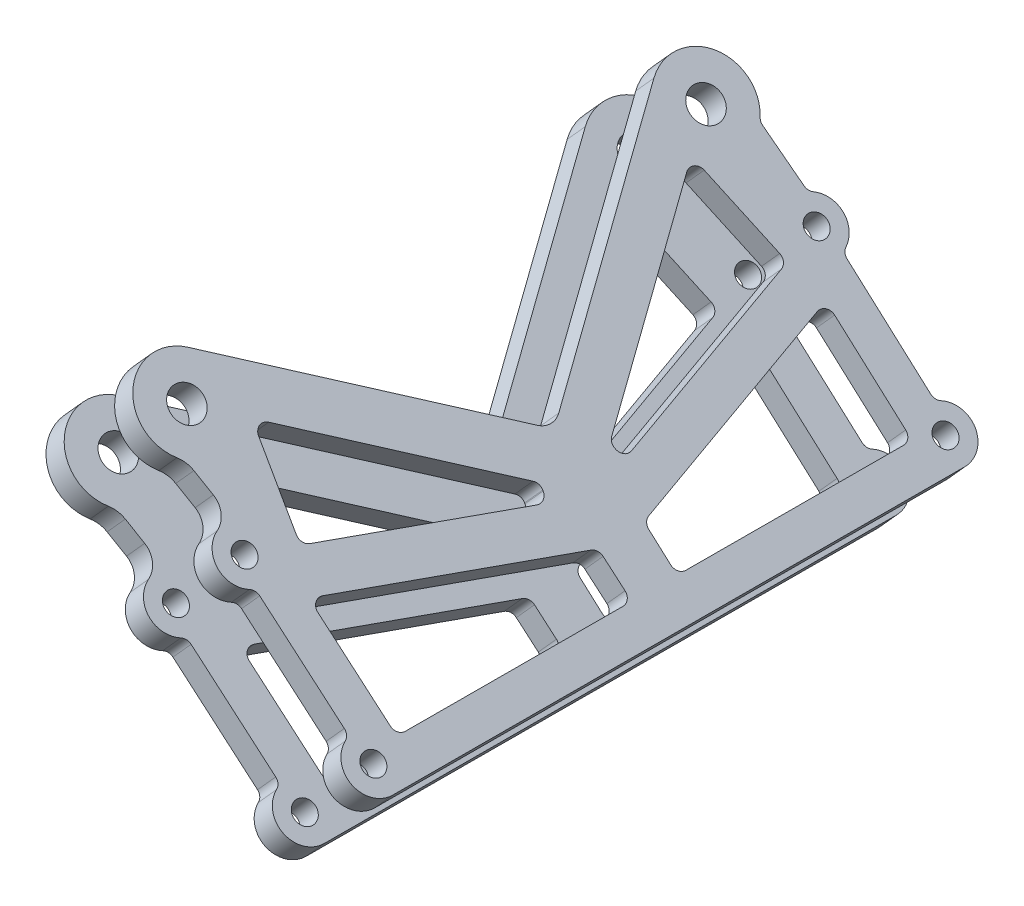
SolidWorks part; units mm, degrees
material "7075-T6, Plate (SS)"
ref_plane "Ground Plane" through (0, 0, 0) normal (0, 0, 1) x (1, 0, 0)
ref_plane "Side Plane" through (0, 0, 0) normal (0, 1, 0) x (1, 0, 0)
ref_plane "Rear Axle Centerline" through (0, 0, 0) normal (1, 0, 0) x (0, 0, -1)
sketch "Chassis Side View" plane through (0, 0, 0) normal (0, 1, 0) x (1, 0, 0)
  line L0 (0, -381) -> (2300, -381) construction
  line L1 (1150, -381) -> (1150, -856.742)
  line L2 (2150, -381) -> (2150, -1062.9307) construction
  line L3 (-753.0356, 0) -> (753.0356, 0) construction
  line L4 (2450, -381) -> (2450, -1062.9307) construction
  dimension "D1" = 2300
  dimension "D2" = 475.742
  dimension "D3" = 1150
  dimension "D4" = 381
  dimension "D5" = 150
  dimension "D6" = 150
ref_plane "Front Axle Centerline" through (2300, 0, 0) normal (1, 0, 0) x (0, 0, -1)
sketch "Front Wheel Assy Constraints" plane through (2300, 0, 0) normal (1, 0, 0) x (0, 0, -1)
  line L0 (0, 727.5) -> (0, 822.5)
  line L1 (0, 822.5) -> (-271.78, 822.5)
  line L2 (-271.78, 822.5) -> (-551.18, 822.5)
  line L3 (-551.18, 822.5) -> (-551.18, 727.5)
  line L4 (-551.18, 775) -> (0, 775) construction
  line L5 (-271.78, 822.5) -> (-271.78, 775) construction
  line L6 (-551.18, 727.5) -> (-445.4516, 727.5)
  line L7 (-445.4516, 727.5) -> (-445.4516, 798.5)
  line L8 (-445.4516, 798.5) -> (-105.7284, 798.5)
  line L9 (-105.7284, 798.5) -> (-105.7284, 727.5)
  line L10 (-105.7284, 727.5) -> (0, 727.5)
  line L11 (0, 0) -> (-673.9047, 0) construction
  line L13 (0, 753.0356) -> (0, -753.0356) construction
  dimension "D1" = 95
  dimension "D2" = 279.4
  dimension "D3" = 271.78
  dimension "D4" = 23.5
  dimension "D5" = 1550
sketch "Front Sus Front View" plane through (2300, 0, 0) normal (1, 0, 0) x (0, 0, -1)
  line L0 (0, 775) -> (0, 768.65) construction
  line L1 (0, 753.0356) -> (0, -753.0356) construction
  line L2 (0, 768.65) -> (-762, 634.2888) construction
  line L3 (0, 768.65) -> (-745.3671, 768.65) construction
  line L4 (-366.7919, -1090.2477) -> (-525.9451, 520.8571) construction
  line L5 (-366.7919, -1090.2477) -> (-379.5678, 520.8571) construction
  line L6 (-366.7919, -1090.2477) -> (0, 775) construction
  line L7 (-525.9451, 520.8571) -> (-541, 673.2571)
  line L8 (-379.5678, 520.8571) -> (-381, 701.4694)
  line L9 (0, 0) -> (-152.4, 0) construction
  line L13 (-525.9451, 520.8571) -> (-379.5678, 520.8571) construction
  dimension "D1" = 6.35
  dimension "D2" = 10
  dimension "D3" = 152.4
  dimension "D4" = 1865.2477
  dimension "D6" = 381
  dimension "D7" = 541
  dimension "D8" = 153.1418
  dimension "D5" = 152.4
ref_plane "Fron Wheel Side View Plane" through (0, 775, 0) normal (0, 1, 0) x (1, 0, 0)
sketch "Front SVSA" plane through (0, 775, 0) normal (0, 1, 0) x (1, 0, 0)
  line L0 (2271.684, -676.7175) -> (2328.316, 133.1575)
  line L1 (2300, 0) -> (2300, -771.0839) construction
  line L2 (2300, 0) -> (-2450.054, -116.0888) construction
  line L3 (-2450.054, -116.0888) -> (2298.2335, -297.0415) construction
  line L4 (-753.0356, 0) -> (753.0356, 0) construction
  point P5 (2300, -271.78)
  dimension "D1" = 4
  dimension "D2" = 1.4
  dimension "D3" = 4750.054
sketch3d "Front Chassis Side Axes"
  line L0 (2300, 520.8571, 379.5678) -> (2300, 701.4694, 381) construction
  line L1 (2300, 520.8571, 525.9451) -> (2300, 673.2571, 541) construction
  line L2 (2300, 520.8571, 379.5678) -> (2300, 701.4694, 381) construction
  line L3 (2300, 520.8571, 525.9451) -> (2300, 673.2571, 541) construction
  line L4 (2300, 673.2571, 541) -> (2300, 775, 551.0507) construction
  line L5 (2300, 701.4694, 381) -> (2300, 775, 381.5831) construction
  line L6 (2300, 775, 0) -> (2300, 775, 771.0839) construction
  line L7 (-2450.054, 775, 116.0888) -> (2349.7917, 775, 555.6101) construction
  line L8 (-2450.054, 775, 116.0888) -> (2349.9221, 775, 384.3734) construction
  line L9 (2349.9221, 775, 384.3734) -> (2177.377, 520.8571, 372.714) construction
  line L10 (2349.7917, 775, 555.6101) -> (2225.4174, 520.8571, 519.1156) construction
  line L11 (2300, 520.8571, 525.9451) -> (2300, 520.8571, 519.1156) construction
  line L12 (2300, 520.8571, 519.1156) -> (2225.4174, 520.8571, 519.1156) construction
  line L13 (2598.7501, 520.8571, 553.3017) -> (1702.4998, 520.8571, 471.2321)
  line L14 (2300, 520.8571, 379.5678) -> (2300, 520.8571, 372.714) construction
  line L15 (2300, 520.8571, 372.714) -> (2177.377, 520.8571, 372.714) construction
  line L16 (2599.5325, 520.8571, 396.3095) -> (1700.935, 520.8571, 346.0843)
  dimension "D1" = 50
  dimension "D2" = 50
  dimension "D3" = 600
  dimension "D4" = 300
  dimension "D5" = 600
  dimension "D6" = 300
sketch3d "Front Left Control Arm"
  line L0 (2300, 520.8571, 379.5678) -> (2300, 701.4694, 381) construction
  line L2 (2300, 520.8571, 379.5678) -> (2300, 701.4694, 381) construction
  line L3 (2300, 520.8571, 525.9451) -> (2300, 673.2571, 541) construction
  line L4 (2598.7501, 520.8571, 553.3017) -> (1702.4998, 520.8571, 471.2321) construction
  line L5 (2599.5325, 520.8571, 396.3095) -> (1700.935, 520.8571, 346.0843) construction
  line L6 (2598.7501, 520.8571, 553.3017) -> (1702.4998, 520.8571, 471.2321) construction
  line L7 (2599.5325, 520.8571, 396.3095) -> (1700.935, 520.8571, 346.0843) construction
  line L8 (2450, 520.8571, 539.6806) -> (2280.5957, 673.2571, 539.2232)
  line L9 (2280.5957, 673.2571, 539.2232) -> (2150, 520.8571, 512.2097)
  line L10 (2300, 520.8571, 525.9451) -> (2300, 673.2571, 541) construction
  line L11 (2300, 673.2571, 541) -> (2280.5957, 673.2571, 539.2232) construction
  line L12 (2271.684, 775, 676.7175) -> (2328.316, 775, -133.1575) construction
  line L13 (2150, 0, 512.2097) -> (2150, 520.8571, 512.2097) construction
  line L14 (2292.3517, 701.4694, 380.5725) -> (2292.3517, 775, 381.1556) construction
  line L15 (2150, 0, 381) -> (2150, 0, 1062.9307) construction
  line L16 (2450, 0, 539.6806) -> (2450, 520.8571, 539.6806) construction
  line L17 (2450, 0, 381) -> (2450, 0, 1062.9307) construction
  line L18 (2450, 520.8571, 387.9517) -> (2292.3517, 701.4694, 380.5725)
  line L19 (2292.3517, 701.4694, 380.5725) -> (2150, 520.8571, 371.1838)
  line L20 (2300, 701.4694, 381) -> (2292.3517, 701.4694, 380.5725) construction
  line L21 (2450, 0, 387.9517) -> (2450, 520.8571, 387.9517) construction
  line L22 (2150, 0, 371.1838) -> (2150, 520.8571, 371.1838) construction
  line L23 (2280.5957, 673.2571, 539.2232) -> (2280.5957, 775, 549.2738) construction
sketch3d "Front Control Arm"
  line L0 (2450, 520.8571, 387.9517) -> (2292.3517, 701.4694, 380.5725) construction
  line L1 (2292.3517, 701.4694, 380.5725) -> (2150, 520.8571, 371.1838) construction
  line L2 (2280.5957, 673.2571, 539.2232) -> (2150, 520.8571, 512.2097) construction
  line L3 (2450, 520.8571, 539.6806) -> (2280.5957, 673.2571, 539.2232) construction
  line L4 (2450, 520.8571, 387.9517) -> (2292.3517, 701.4694, 380.5725)
  line L5 (2292.3517, 701.4694, 380.5725) -> (2150, 520.8571, 371.1838)
  line L6 (2280.5957, 673.2571, 539.2232) -> (2150, 520.8571, 512.2097)
  line L7 (2450, 520.8571, 539.6806) -> (2280.5957, 673.2571, 539.2232)
  line L8 (2450, -520.8571, 539.6806) -> (2280.5957, -673.2571, 539.2232)
  line L9 (2280.5957, -673.2571, 539.2232) -> (2150, -520.8571, 512.2097)
  line L10 (2292.3517, -701.4694, 380.5725) -> (2150, -520.8571, 371.1838)
  line L11 (2450, -520.8571, 387.9517) -> (2292.3517, -701.4694, 380.5725)
ref_plane "Max Droop Plane" through (0, 0, -25.4) normal (0, 0, 1) x (1, 0, 0)
sketch3d "Shock"
  line L0 (2292.3517, 701.4694, 380.5725) -> (2293.5626, 664.4705, 414.2387) construction
  line L1 (2300, 520.8571, 525.9451) -> (2298.2629, 520.8571, 544.9158) construction
  line L2 (2150, 520.8571, 512.2097) -> (2450, 520.8571, 539.6806) construction
  line L3 (2300, 520.8571, 525.9451) -> (2300, 230.5152, 525.9451) construction
  line L4 (2293.5626, 664.4705, 414.2387) -> (2298.2629, 520.8571, 544.9158)
  dimension "D1" = 50.038
  dimension "D2" = 19.05
sketch3d "Parametric Analysis"
  line L2 (2300, 822.5, 0) -> (2300, 822.5, 271.78) construction
  line L3 (2300.4137, 822.5, 271.7939) -> (2300.4137, 822.5, -88.8537) construction
  line L4 (2450, 520.8571, 387.9517) -> (2292.3526, 701.4695, 380.5568)
  line L5 (2292.3526, 701.4695, 380.5568) -> (2150, 520.8571, 371.1838)
  line L6 (2450, 520.8571, 539.6806) -> (2280.5972, 673.2586, 539.2077)
  line L7 (2280.5972, 673.2586, 539.2077) -> (2150, 520.8571, 512.2097)
  line L8 (2292.3517, 701.4694, 380.5725) -> (2300, 822.5, 271.78) construction
  line L9 (2450, 520.8571, 387.9517) -> (2292.3517, 701.4694, 380.5725) construction
  line L10 (2292.3517, 701.4694, 380.5725) -> (2150, 520.8571, 371.1838) construction
  line L11 (2450, 520.8571, 539.6806) -> (2280.5957, 673.2571, 539.2232) construction
  line L12 (2280.5957, 673.2571, 539.2232) -> (2150, 520.8571, 512.2097) construction
  line L13 (2280.5957, 673.2571, 539.2232) -> (2292.3517, 701.4694, 380.5725) construction
  line L14 (2300, 822.5, 271.78) -> (2280.5957, 673.2571, 539.2232) construction
  line L15 (2300, 822.5, 271.78) -> (2300.4132, 720.8156, 271.78) construction
  line L16 (2280.5972, 673.2586, 539.2077) -> (2300.4137, 822.5, 271.7939) construction
  line L17 (2300.4137, 822.5, 271.7939) -> (2292.3526, 701.4695, 380.5568) construction
  line L18 (2280.5972, 673.2586, 539.2077) -> (2292.3526, 701.4695, 380.5568) construction
  line L19 (2300.4137, 822.5, 271.7939) -> (2300.4137, 720.8148, 271.7641) construction
  line L23 (2292.3517, 701.4694, 380.5725) -> (2265.8007, 667.7821, 378.8214) construction
  line L30 (2265.8007, 667.7821, 378.8214) -> (2325.2406, 663.7898, 382.112) construction
  line L31 (2325.2406, 663.7898, 382.112) -> (2293.5626, 664.4705, 414.2387) construction
  line L32 (2292.3517, 701.4694, 380.5725) -> (2325.2406, 663.7898, 382.112) construction
  line L33 (2293.5626, 664.4705, 414.2387) -> (2265.8007, 667.7821, 378.8214) construction
  line L34 (2292.3526, 701.4695, 380.5568) -> (2293.5633, 664.4722, 414.2247) construction
  line L35 (2292.3517, 701.4694, 380.5725) -> (2293.5626, 664.4705, 414.2387) construction
  line L39 (2300.4137, 822.5, 271.7939) -> (2300.4137, 822.5798, 0.014)
  line L40 (2300.4137, 822.5798, 0.014) -> (2300.4137, 727.5798, -0.014)
  line L41 (2300, 727.5, 0) -> (2300, 822.5, 0) construction
  line L42 (2298.2629, 520.8571, 544.9158) -> (2293.5633, 664.4722, 414.2247)
  point P5 (2300.4137, 775.0798, 0)
  dimension "D1" = 25.4
  dimension "D2" = 194.2357
  dimension "D3" = 0.0798
  dimension "D4" = 0.017
sketch3d "3DSketch1"
  line L0 (2293.5626, 664.4705, 414.2387) -> (2298.2629, 520.8571, 544.9158) construction
  line L1 (2280.5972, 673.2586, 539.2077) -> (2150, 520.8571, 512.2097) construction
  line L2 (2450, 520.8571, 539.6806) -> (2280.5972, 673.2586, 539.2077) construction
  line L3 (2292.3526, 701.4695, 380.5568) -> (2150, 520.8571, 371.1838) construction
  line L4 (2450, 520.8571, 387.9517) -> (2292.3526, 701.4695, 380.5568) construction
  line L5 (2293.5626, 664.4705, 414.2387) -> (2298.2629, 520.8571, 544.9158)
  line L6 (2280.5972, 673.2586, 539.2077) -> (2150, 520.8571, 512.2097)
  line L7 (2450, 520.8571, 539.6806) -> (2280.5972, 673.2586, 539.2077)
  line L8 (2292.3526, 701.4695, 380.5568) -> (2150, 520.8571, 371.1838)
  line L9 (2450, 520.8571, 387.9517) -> (2292.3526, 701.4695, 380.5568)
  line L10 (2450, 520.8571, 539.6806) -> (2450, 470.0571, 539.6806) construction
  line L11 (2150, 520.8571, 512.2097) -> (2150, 470.0571, 512.2097) construction
  line L12 (2298.2629, 520.8571, 544.9158) -> (2298.2629, 470.0571, 544.9158) construction
  line L13 (2450, 520.8571, 387.9517) -> (2450, 470.0571, 387.9517) construction
  line L14 (2150, 520.8571, 371.1838) -> (2150, 470.0571, 371.1838) construction
  line L15 (2150, -520.8571, 512.2097) -> (2150, -470.0571, 512.2097) construction
  line L16 (2298.2629, -520.8571, 544.9158) -> (2298.2629, -470.0571, 544.9158) construction
  line L17 (2450, -520.8571, 539.6806) -> (2450, -470.0571, 539.6806) construction
  line L18 (2293.5626, -664.4705, 414.2387) -> (2298.2629, -520.8571, 544.9158)
  line L19 (2280.5972, -673.2586, 539.2077) -> (2150, -520.8571, 512.2097)
  line L20 (2450, -520.8571, 539.6806) -> (2280.5972, -673.2586, 539.2077)
  line L21 (2450, -520.8571, 387.9517) -> (2450, -470.0571, 387.9517) construction
  line L22 (2150, -520.8571, 371.1838) -> (2150, -470.0571, 371.1838) construction
  line L23 (2292.3526, -701.4695, 380.5568) -> (2150, -520.8571, 371.1838)
  line L24 (2450, -520.8571, 387.9517) -> (2292.3526, -701.4695, 380.5568)
  line L25 (2280.5972, 673.2586, 539.2077) -> (2280.5972, 673.2586, 216.3834) construction
  line L26 (2450, 520.8571, 539.6806) -> (2457.3728, 529.0523, 539.6794) construction
  line L27 (2300, 775, 551.18) -> (2300, 775, 0) construction
  line L29 (2457.3728, 529.0523, 539.6794) -> (2420.3829, 562.3299, 539.5762) construction
  dimension "D1" = 50.8
  dimension "D2" = 304.9478
  dimension "D3" = 544.9185
  dimension "D4" = 11.0236
ref_plane "Plane1" through (0, 718.612, 0) normal (0, 1, 0) x (1, 0, 0)
ref_plane "Plane2" through (1354.9026, 1506.0502, 0) normal (0.6688, 0.7434, 0) x (-0.7434, 0.6688, -0.0021)
sketch "Sketch1" plane through (1354.9026, 1506.0502, 0) normal (0.6688, 0.7434, 0) x (-0.7434, 0.6688, -0.0021)
  line L0 (-1474.1559, 536.6223) -> (-1473.841, 384.8937) construction
  line L1 (-1474.1559, 536.6223) -> (-1474.1559, 558.2123) construction
  line L2 (-1452.5659, 536.6223) -> (-1474.1559, 558.2123)
  line L3 (-1474.1559, 536.6223) -> (-1246.288, 536.6223) construction
  line L4 (-1474.1559, 558.2123) -> (-1575.7559, 558.2123)
  line L5 (-1575.7559, 558.2123) -> (-1575.7559, 363.3037)
  line L10 (-1474.1559, 536.6223) -> (-1452.5659, 536.6223) construction
  line L11 (-1473.841, 384.8937) -> (-1435.1122, 384.9741) construction
  line L12 (-1473.841, 384.8937) -> (-1507.8168, 384.8232) construction
  line L13 (-1452.5659, 536.6223) -> (-1452.5659, 384.9379)
  line L15 (-1473.841, 384.8937) -> (-1473.841, 363.3037) construction
  line L16 (-1575.7559, 363.3037) -> (-1473.841, 363.3037)
  line L17 (-1473.841, 363.3037) -> (-1452.5659, 384.9379)
  line L18 (-1445.7366, 460.758) -> (-1502.2603, 460.758) construction
  circle A0 centre (-1474.1559, 536.6223) radius 4.7625
  circle A1 centre (-1473.841, 384.8937) radius 4.7625
  circle A2 centre (-1557.9759, 544.2423) radius 3.175
  circle A3 centre (-1507.1759, 544.2423) radius 3.175
  circle A4 centre (-1507.1759, 377.2737) radius 3.175
  circle A5 centre (-1557.9759, 377.2737) radius 3.175
  circle A6 centre (-1532.5759, 460.758) radius 3.175
  point P22 (-1473.9984, 460.758)
  point P31 (-1532.5759, 460.758)
  dimension "D1" = 9.525
  dimension "D2" = 9.525
  dimension "D7" = 6.35
  dimension "D10" = 6.35
  dimension "D12" = 6.35
  dimension "D3" = 21.59
  dimension "D4" = 21.59
  dimension "D5" = 21.59
  dimension "D6" = 101.6
  dimension "D8" = 17.78
  dimension "D9" = 13.97
  dimension "D11" = 50.8
  dimension "D13" = 43.18
  dimension "D14" = 97.4543
extrude "Boss-Extrude1" add sketch "Sketch1" along normal blind 18.9611 and the other way blind 18.9611
ref_plane "Cut Plane" through (1367.5841, 1520.1464, 0) normal (0.6688, 0.7434, 0) x (0.7434, -0.6688, 0)
sketch "Sketch2" plane through (1367.5841, 1520.1464, 0) normal (0.6688, 0.7434, 0) x (0.7434, -0.6688, 0)
  line L0 (1556.843, -547.4746) -> (1531.6163, -463.9377) construction
  line L1 (1531.6163, -463.9377) -> (1506.0431, -547.3691) construction
  line L2 (1506.0431, -547.3691) -> (1473.039, -539.6806) construction
  line L3 (1531.6163, -463.9377) -> (1557.1895, -380.5063) construction
  line L4 (1531.6163, -463.9377) -> (1506.3896, -380.4009) construction
  line L5 (1506.3896, -380.4009) -> (1473.039, -387.9517) construction
  line L6 (1473.039, -387.9517) -> (1531.6163, -463.9377) construction
  line L7 (1531.6163, -463.9377) -> (1473.039, -539.6806) construction
  line L8 (1564.8095, -380.5063) -> (1564.463, -547.4746)
  line L9 (1506.0431, -547.3691) -> (1513.3285, -549.6023) construction
  line L10 (1506.0431, -547.3691) -> (1498.7577, -545.136) construction
  line L11 (1473.039, -539.6806) -> (1462.9928, -531.9112) construction
  line L12 (1515.3747, -378.198) -> (1548.2609, -378.198)
  line L13 (1513.6843, -378.198) -> (1499.095, -382.6038) construction
  line L14 (1483.0972, -380.1979) -> (1462.9808, -395.7055) construction
  line L16 (1492.0841, -546.1214) -> (1485.7226, -547.0606)
  line L18 (1482.702, -378.5846) -> (1497.8198, -377.7153)
  line L19 (1507.8037, -533.5519) -> (1486.2159, -528.5229)
  line L28 (1462.9928, -531.9112) -> (1513.1623, -467.04)
  line L29 (1513.1677, -460.8314) -> (1462.9808, -395.7055)
  line L30 (1484.7829, -524.4953) -> (1522.7158, -475.4465)
  line L31 (1525.3013, -474.5266) -> (1525.5167, -474.5767)
  line L32 (1527.3689, -477.7949) -> (1510.8084, -531.8225)
  line L33 (1507.4206, -391.9812) -> (1484.6718, -397.1317)
  line L34 (1483.221, -401.1598) -> (1522.7938, -452.4933)
  line L35 (1525.3664, -453.4198) -> (1525.5847, -453.3704)
  line L36 (1527.4553, -450.1588) -> (1510.413, -393.7242)
  line L37 (1574.594, -561.4814) -> (1472.9942, -561.2706)
  line L38 (1472.9942, -561.2706) -> (1451.449, -539.6358)
  line L39 (1451.449, -539.6358) -> (1451.7638, -387.9517)
  line L40 (1451.7638, -387.9517) -> (1473.0838, -366.3618)
  line L41 (1473.0838, -366.3618) -> (1574.9985, -366.5733)
  line L42 (1574.9985, -366.5733) -> (1574.594, -561.4814)
  line L43 (1514.9847, -549.5748) -> (1547.5052, -549.0356)
  arc A1 (1512.7809, -550.9281) -> (1498.935, -550.115) centre (1506.0431, -547.3691) cw
  arc A2 (1462.9928, -531.9112) -> (1481.6619, -549.0046) centre (1473.039, -539.6806) ccw
  arc A4 (1513.1284, -376.8438) -> (1499.8529, -376.4848) centre (1506.3896, -380.4009) ccw
  arc A5 (1462.9808, -395.7055) -> (1480.97, -378.0326) centre (1473.039, -387.9517) cw
  arc A8 (1492.0841, -546.1214) -> (1498.935, -550.115) centre (1493.0117, -552.4033) cw
  arc A9 (1481.6619, -549.0046) -> (1485.7226, -547.0606) centre (1486.8356, -554.5989) cw
  arc A10 (1484.7829, -524.4953) -> (1486.2159, -528.5229) centre (1486.7921, -526.0491) ccw
  arc A11 (1507.8037, -533.5519) -> (1510.8084, -531.8225) centre (1508.3799, -531.0782) ccw
  arc A12 (1527.3689, -477.7949) -> (1525.5167, -474.5767) centre (1524.9404, -477.0505) ccw
  arc A13 (1525.3013, -474.5266) -> (1522.7158, -475.4465) centre (1524.725, -477.0003) ccw
  arc A14 (1510.413, -393.7242) -> (1507.4206, -391.9812) centre (1507.9815, -394.4585) ccw
  arc A15 (1484.6718, -397.1317) -> (1483.221, -401.1598) centre (1485.2327, -399.609) ccw
  arc A16 (1522.7938, -452.4933) -> (1525.3664, -453.4198) centre (1524.8055, -450.9425) ccw
  arc A17 (1525.5847, -453.3704) -> (1527.4553, -450.1588) centre (1525.0238, -450.8931) ccw
  arc A19 (1513.1623, -467.04) -> (1513.1677, -460.8314) centre (1509.1438, -463.9322) ccw
  arc A22 (1499.8529, -376.4848) -> (1497.8198, -377.7153) centre (1497.674, -375.1795) cw
  arc A23 (1482.702, -378.5846) -> (1480.97, -378.0326) centre (1482.5562, -376.0488) cw
  circle A24 centre (1557.1895, -380.5063) radius 7.62 construction
  circle A25 centre (1556.843, -547.4746) radius 7.62 construction
  arc A26 (1549.8712, -550.5501) -> (1564.463, -547.4746) centre (1556.843, -547.4746) ccw
  arc A27 (1564.8095, -380.5063) -> (1550.4931, -376.8701) centre (1557.1895, -380.5063) ccw
  arc A28 (1549.8712, -550.5501) -> (1547.5052, -549.0356) centre (1547.5473, -551.5753) ccw
  arc A29 (1514.9847, -549.5748) -> (1512.7809, -550.9281) centre (1515.0269, -552.1144) ccw
  arc A30 (1550.4931, -376.8701) -> (1548.2609, -378.198) centre (1548.2609, -375.658) cw
  arc A31 (1515.3747, -378.198) -> (1513.1284, -376.8438) centre (1515.3747, -375.658) cw
  point P17 (1556.843, -547.4746)
  point P25 (1557.1895, -380.5063)
  point P29 (1506.3896, -380.4009)
  point P33 (1473.039, -387.9517)
  point P36 (1483.0972, -380.1979)
  point P37 (1499.291, -377.6307)
  point P39 (1499.095, -382.6038)
  point P48 (1531.6163, -463.9377)
  point P52 (1531.6163, -463.9377)
  point P54 (1531.6163, -463.9377)
  point P62 (1482.3623, -527.6252)
  point P65 (1510.1134, -534.09)
  point P68 (1528.1661, -475.1939)
  point P71 (1523.7133, -474.1566)
  point P74 (1509.7289, -391.4586)
  point P77 (1480.7928, -398.0099)
  point P80 (1523.7842, -453.778)
  point P83 (1528.2434, -452.7685)
  point P84 (1549.3782, -549.0046)
  point P89 (1515.5615, -463.9377)
  point P93 (1549.9276, -378.198)
  point P109 (1481.6788, -378.6434)
  dimension "D2" = 7.62
  dimension "D3" = 12.7
  dimension "D4" = 15.24
  dimension "D5" = 7.62
  dimension "D6" = 12.7
  dimension "D7" = 25.3127
  dimension "D8" = 17.6413
  dimension "D9" = 6.35
  dimension "D10" = 7.62
  dimension "D23" = 2.54
  dimension "D26" = 2.54
  dimension "D11" = 15.24
  dimension "D13" = 2.54
  dimension "D12" = 36.0496
  dimension "D14" = 20.127
  dimension "D15" = 86.1415
  dimension "D18" = 85.9294
  dimension "D19" = 15.24
  dimension "D20" = 4.572
  dimension "D21" = 12.7
  dimension "D22" = 4.572
extrude "Cut-Extrude1" cut sketch "Sketch2" against normal through all
ref_plane "Plane4" through (871.9396, -784.4315, 907.0589) normal (-0.5881, 0.5291, -0.6118) x (-0.8088, -0.3847, 0.4448)
sketch "Sketch3" plane through (871.9396, -784.4315, 907.0589) normal (-0.5881, 0.5291, -0.6118) x (-0.8088, -0.3847, 0.4448)
  line L0 (-1941.8721, 746.988) -> (-1958.1391, 723.0664) construction
  line L2 (-1938.9644, 770.8679) -> (-1920.7331, 758.4704)
  line L3 (-1926.1928, 736.3259) -> (-1957.5515, 757.6502) construction
  line L4 (-1938.9644, 770.8679) -> (-2068.0084, 581.1008)
  line L5 (-2068.0084, 581.1008) -> (-2049.7771, 568.7032)
  line L6 (-2049.7771, 568.7032) -> (-1920.7331, 758.4704)
  point P8 (-1941.8721, 746.988)
  point P9 (-1929.8488, 764.6691)
  dimension "D1" = 11.0236
extrude "Cut-Extrude3" cut sketch "Sketch3" against normal through all both and the other way through all
sketch "Sketch4" plane through (1367.5841, 1520.1464, 0) normal (0.6688, 0.7434, 0) x (0.7434, -0.6688, 0)
  line L0 (1524.1527, -388.358) -> (1552.0879, -388.358)
  line L1 (1515.3747, -378.198) -> (1548.2609, -378.198) construction
  line L5 (1521.7211, -391.6323) -> (1540.897, -455.1323)
  line L6 (1543.3286, -456.938) -> (1551.9561, -456.938)
  line L7 (1554.4961, -454.4033) -> (1554.6279, -390.9033)
  line L8 (1523.9594, -539.2646) -> (1551.8283, -538.8025)
  line L12 (1521.4888, -535.9806) -> (1541.0512, -472.1593)
  line L13 (1543.4375, -470.364) -> (1551.8759, -470.2241)
  line L14 (1514.9847, -549.5748) -> (1547.5052, -549.0356) construction
  line L15 (1554.458, -472.769) -> (1554.3262, -536.2682)
  line L17 (1527.4553, -450.1588) -> (1510.413, -393.7242) construction
  line L18 (1564.8095, -380.5063) -> (1564.463, -547.4746) construction
  line L19 (1527.3689, -477.7949) -> (1510.8084, -531.8225) construction
  arc A0 (1551.8759, -470.2241) -> (1554.458, -472.769) centre (1551.918, -472.7638) cw
  arc A1 (1554.3262, -536.2682) -> (1551.8283, -538.8025) centre (1551.7862, -536.2629) cw
  arc A2 (1523.9594, -539.2646) -> (1521.4888, -535.9806) centre (1523.9173, -536.725) cw
  arc A3 (1541.0512, -472.1593) -> (1543.4375, -470.364) centre (1543.4796, -472.9037) cw
  arc A4 (1554.4961, -454.4033) -> (1551.9561, -456.938) centre (1551.9561, -454.398) cw
  arc A5 (1543.3286, -456.938) -> (1540.897, -455.1323) centre (1543.3286, -454.398) cw
  arc A6 (1552.0879, -388.358) -> (1554.6279, -390.9033) centre (1552.0879, -390.898) cw
  arc A7 (1524.1527, -388.358) -> (1521.7211, -391.6323) centre (1524.1527, -390.898) ccw
  point P20 (1554.4634, -470.1812)
  point P23 (1554.3211, -538.7612)
  point P30 (1554.4909, -456.938)
  point P35 (1554.6332, -388.358)
  dimension "D9" = 2.54
  dimension "D1" = 10.16
  dimension "D2" = 11.43
  dimension "D3" = 10.16
  dimension "D4" = 68.58
  dimension "D5" = 10.16
  dimension "D6" = 11.43
  dimension "D7" = 68.58
  dimension "D8" = 10.16
extrude "Cut-Extrude4" cut sketch "Sketch4" against normal through all both and the other way through all
sketch "Sketch5" plane through (871.9396, -784.4315, 907.0589) normal (-0.5881, 0.5291, -0.6118) x (-0.8088, -0.3847, 0.4448)
  line L0 (-1913.8851, 757.3814) -> (-2035.4717, 578.5808)
  line L1 (-2035.4717, 578.5808) -> (-2029.4281, 574.4711)
  line L2 (-2029.4281, 574.4711) -> (-1907.8415, 753.2717)
  line L3 (-1907.8415, 753.2717) -> (-1913.8851, 757.3814)
  line L4 (-1926.1928, 736.3259) -> (-1972.3071, 668.512) construction
  line L5 (-1919.0513, 746.8278) -> (-1925.615, 751.2912) construction
sketch "Sketch6" plane through (1367.5841, 1520.1464, 0) normal (0.6688, 0.7434, 0) x (0.7434, -0.6688, 0)
  circle A0 centre (1531.6163, -463.9377) radius 3.175
  dimension "D1" = 6.35
extrude "Boss-Extrude2" add sketch "Sketch6" against normal up to surface (7.9375 mm away) up to face at (2509.2303, 482.3993, 504.5053)
sketch "Sketch7" plane through (1342.2211, 1491.954, 0) normal (-0.6688, -0.7434, 0) x (0.7434, -0.6688, 0)
  circle A0 centre (1531.6163, 463.9377) radius 3.175
  dimension "D1" = 6.35
extrude "Boss-Extrude3" add sketch "Sketch7" against normal up to surface (7.9375 mm away) up to face at (2494.4847, 466.0088, 504.5053)
equation "\"wheelbase\"= 2.3m"
equation "\"track_front_outer\"= 1.55m"
equation "\"cg_h\"= 18.73in"
equation "\"cg_b\"= \"wheelbase\" / 2"
equation "\"chassis_ride_height\"= 15in"
equation "\"hub_offset\"= 23.5mm"
equation "\"tire_radius\"= 11in"
equation "\"tire_radius_loaded\"= 10.7in"
equation "\"tire_width\"= 95mm"
equation "\"static_camber\"= 0deg"
equation "\"caster_static\"= 4deg"
equation "\"control_arm_ratio\"= 0.95"
equation "\"roll_center_height\"= 6in"
equation "\"scrub_radius\"= 0.25in"
equation "\"camber_change_rate\"= 0.5deg'per inch of travel"
equation "\"fvsa_length\"= atn ( 1 / \"camber_change_rate\" )"
equation "\"svsa_length\"= 2.5 * \"wheelbase\""
equation "\"svsa_height\"= 1"
equation "\"anti_squat_rear\"= 0.15"
equation "\"front_brakes\"= .75"
equation "\"anti_dive_front\"= 0.1"
equation "\"D1@Chassis Side View\" = \"wheelbase\""
equation "\"D2@Chassis Side View\" = \"cg_h\""
equation "\"D3@Chassis Side View\" = \"cg_b\""
equation "\"D4@Chassis Side View\" = \"chassis_ride_height\""
equation "\"D1@Front Axle Centerline\"=\"wheelbase\""
equation "\"D1@Front Wheel Assy Constraints\" = \"tire_width\""
equation "\"D2@Front Wheel Assy Constraints\" = \"tire_radius\""
equation "\"D3@Front Wheel Assy Constraints\" = \"tire_radius_loaded\""
equation "\"D4@Front Wheel Assy Constraints\" = \"hub_offset\""
equation "\"D1@Front Sus Front View\" = \"scrub_radius\""
equation "\"static_kingpin\"= 10deg"
equation "\"D2@Front Sus Front View\" = \"static_kingpin\""
equation "\"D3@Front Sus Front View\" = \"roll_center_height\""
equation "\"D6@Front Sus Front View\" = \"chassis_ride_height\""
equation "\"D7@Front Sus Front View\"=\"chassis_ride_height\" + 160mm"
equation "\"D1@Front SVSA\" = \"caster_static\""
equation "\"D4@Front Sus Front View\"=\"fvsa_length\"+10"
equation "\"D5@Front Wheel Assy Constraints\"=\"track_front_outer\""
equation "\"phi_front\"= atn ( \"anti_dive_front\" / \"front_brakes\" * \"cg_h\" / \"wheelbase\" )"
equation "\"anti_lift_rear\"= 0.1"
equation "\"a\"= 0"
